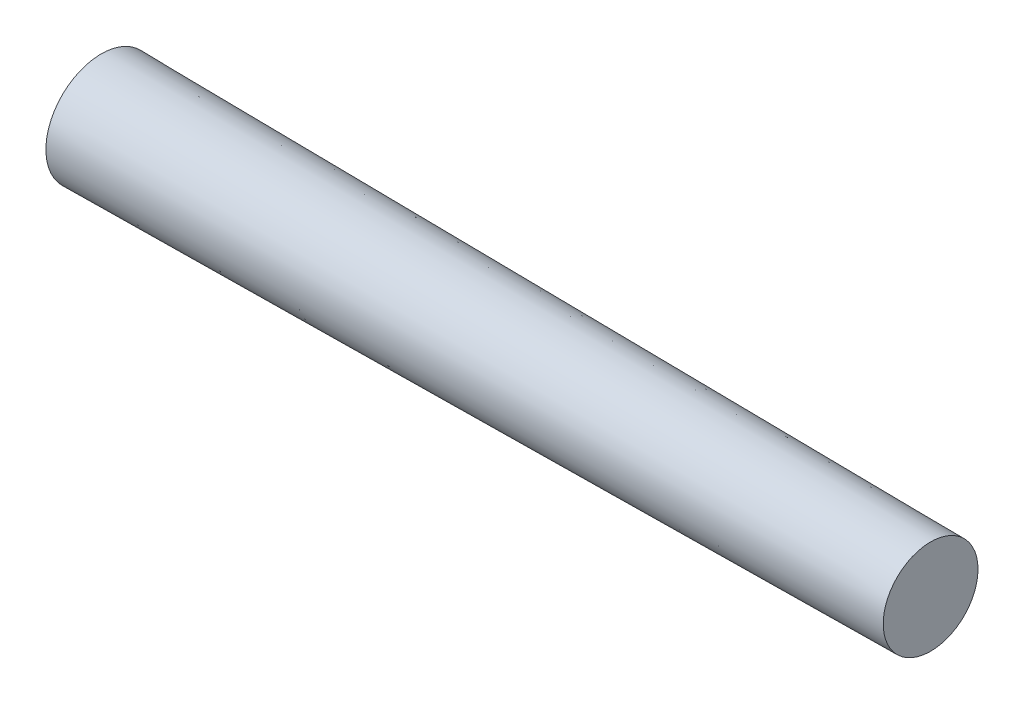
SolidWorks part; units mm, degrees
material "Ti-5Al-2.5Sn Annealed (SS)"
ref_plane "Front Plane" through (0, 0, 0) normal (0, 0, 1) x (1, 0, 0)
ref_plane "Top Plane" through (0, 0, 0) normal (0, 1, 0) x (1, 0, 0)
ref_plane "Right Plane" through (0, 0, 0) normal (1, 0, 0) x (0, 0, -1)
sketch "Sketch1" plane through (0, 0, 0) normal (1, 0, 0) x (0, 0, -1)
  line L0 (0, -7) -> (0, 7) construction
  line L1 (-7, 0) -> (7, 0) construction
  circle A0 centre (0, 0) radius 7
  dimension "D1" = 14
ref_plane "Plane1" through (105, 0, 0) normal (1, 0, 0) x (0, 0, -1)
sketch "Sketch2" plane through (105, 0, 0) normal (1, 0, 0) x (0, 0, -1)
  line L0 (-6, 0) -> (6, 0) construction
  line L1 (0, 6) -> (0, -6) construction
  circle A0 centre (0, 0) radius 6
  dimension "D1" = 12
loft "Loft2" add profiles "Sketch2", "Sketch1"
equation "\"1g\"=2"
